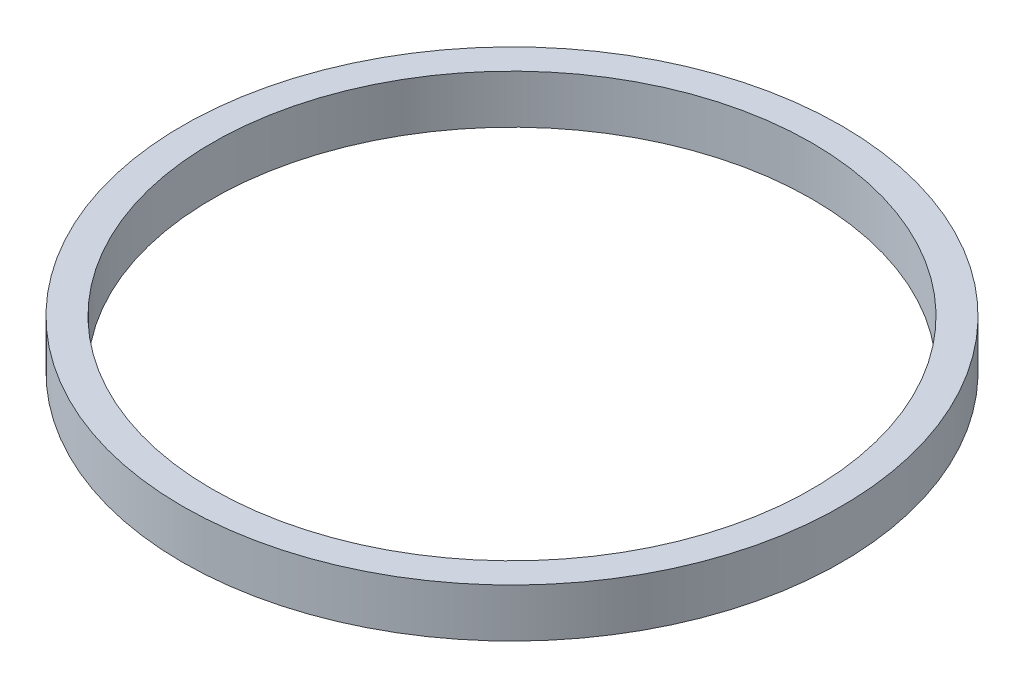
SolidWorks part; units mm, degrees
material "EPİKLORHİDRİN"
ref_plane "Ön Düzlem" through (0, 0, 0) normal (0, 0, 1) x (1, 0, 0)
ref_plane "Üst Düzlem" through (0, 0, 0) normal (0, 1, 0) x (1, 0, 0)
ref_plane "Sağ Düzlem" through (0, 0, 0) normal (1, 0, 0) x (0, 0, -1)
sketch "Çizim1" plane through (0, 0, 0) normal (0, 1, 0) x (1, 0, 0)
  circle A0 centre (0, 0) radius 18.87
extrude "Yükseklik-Ekstrüzyon1" add sketch "Çizim1" along normal blind 2.78
sketch "Çizim2" plane through (0, 2.78, 0) normal (0, 1, 0) x (1, 0, 0)
  circle A0 centre (0, 0) radius 17.17
extrude "Kes-Ekstrüzyon1" cut sketch "Çizim2" against normal blind 5.78 and the other way blind 4
